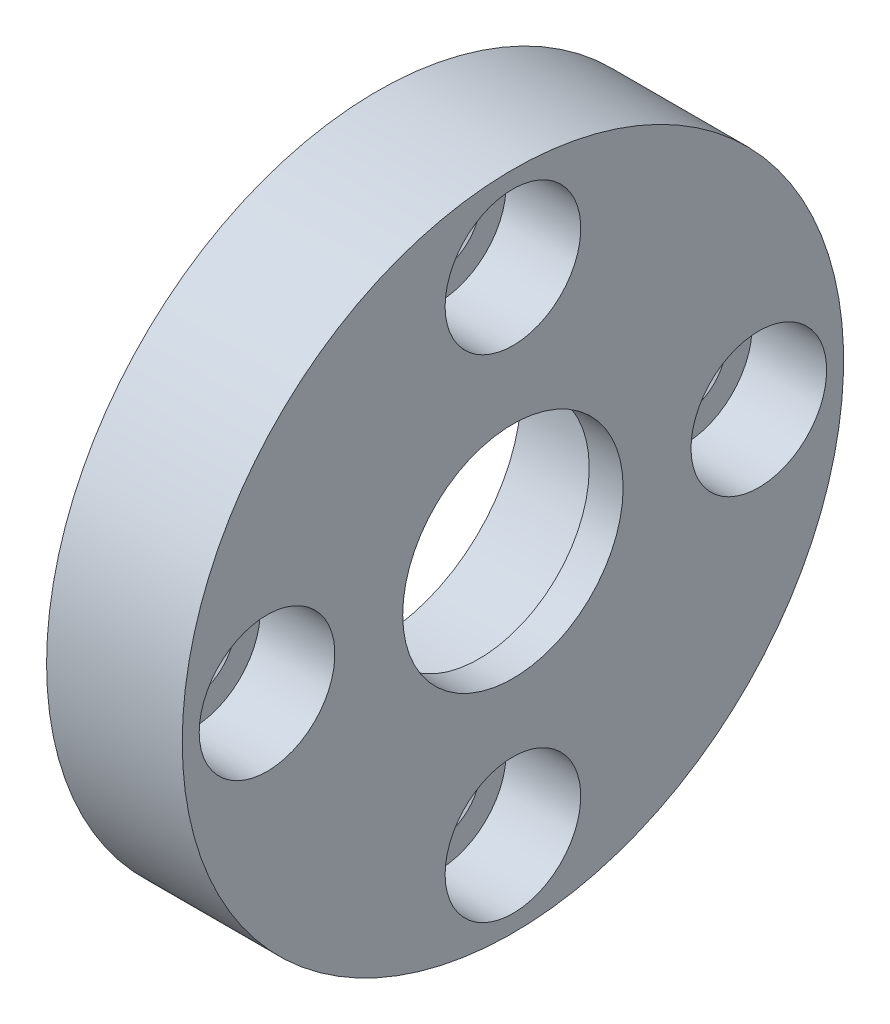
SolidWorks part; units mm, degrees
ref_plane "正面" through (0, 0, 0) normal (0, 0, 1) x (1, 0, 0)
ref_plane "平面" through (0, 0, 0) normal (0, 1, 0) x (1, 0, 0)
ref_plane "右側面" through (0, 0, 0) normal (1, 0, 0) x (0, 0, -1)
ref_plane "平面1" through (0, 0, 0) normal (0, 0, 1) x (1, 0, 0)
sketch "ｽｹｯﾁ1" plane through (0, 0, 0) normal (0, 0, 1) x (1, 0, 0)
  line L0 (-4, 0) -> (-4, 19.5)
  line L1 (-4, 19.5) -> (4, 19.5)
  line L2 (4, 19.5) -> (4, 0)
  line L3 (4, 0) -> (-4, 0)
  line L4 (4, 0) -> (-4, 0) construction
revolve "回転1" add sketch "ｽｹｯﾁ1" angle 360 about L4
ref_plane "平面2" through (0, 0, 0) normal (0, 0, 1) x (1, 0, 0)
sketch "ｽｹｯﾁ2" plane through (0, 0, 0) normal (0, 0, 1) x (1, 0, 0)
  line L0 (-4, 0) -> (-4, 8.5)
  line L1 (-4, 8.5) -> (2, 8.5)
  line L2 (2, 8.5) -> (2, 6.5)
  line L3 (2, 6.5) -> (4, 6.5)
  line L4 (4, 6.5) -> (4, 0)
  line L5 (4, 0) -> (-4, 0)
  line L6 (4, 0) -> (-4, 0) construction
revolve "ｶｯﾄ - 回転1" cut sketch "ｽｹｯﾁ2" angle 360 about L6
ref_plane "平面3" through (0, 0, 0) normal (0, 0, 1) x (1, 0, 0)
sketch "ｽｹｯﾁ3" plane through (0, 0, 0) normal (0, 0, 1) x (1, 0, 0)
  line L0 (-4, 14.5) -> (-4, 17)
  line L1 (-4, 17) -> (-3.567, 16.567)
  line L2 (-3.567, 16.567) -> (-0.833, 16.567)
  line L3 (-0.833, 16.567) -> (-0.4, 17)
  line L4 (-0.4, 17) -> (-0.4, 18.5)
  line L5 (-0.4, 18.5) -> (4, 18.5)
  line L6 (4, 18.5) -> (4, 14.5)
  line L7 (4, 14.5) -> (-4, 14.5)
  line L8 (4, 14.5) -> (-4, 14.5) construction
revolve "ｶｯﾄ - 回転2" cut sketch "ｽｹｯﾁ3" angle 360 about L8
ref_plane "平面4" through (0, 0, 14.5) normal (0, 0, 1) x (1, 0, 0)
sketch "ｽｹｯﾁ4" plane through (0, 0, 14.5) normal (0, 0, 1) x (1, 0, 0)
  line L0 (-4, 0) -> (-4, 2.5)
  line L1 (-4, 2.5) -> (-3.567, 2.067)
  line L2 (-3.567, 2.067) -> (-0.833, 2.067)
  line L3 (-0.833, 2.067) -> (-0.4, 2.5)
  line L4 (-0.4, 2.5) -> (-0.4, 4)
  line L5 (-0.4, 4) -> (4, 4)
  line L6 (4, 4) -> (4, 0)
  line L7 (4, 0) -> (-4, 0)
  line L8 (4, 0) -> (-4, 0) construction
revolve "ｶｯﾄ - 回転3" cut sketch "ｽｹｯﾁ4" angle 360 about L8
ref_plane "平面5" through (0, 0, 0) normal (0, 0, 1) x (1, 0, 0)
sketch "ｽｹｯﾁ5" plane through (0, 0, 0) normal (0, 0, 1) x (1, 0, 0)
  line L0 (-4, -14.5) -> (-4, -12)
  line L1 (-4, -12) -> (-3.567, -12.433)
  line L2 (-3.567, -12.433) -> (-0.833, -12.433)
  line L3 (-0.833, -12.433) -> (-0.4, -12)
  line L4 (-0.4, -12) -> (-0.4, -10.5)
  line L5 (-0.4, -10.5) -> (4, -10.5)
  line L6 (4, -10.5) -> (4, -14.5)
  line L7 (4, -14.5) -> (-4, -14.5)
  line L8 (4, -14.5) -> (-4, -14.5) construction
revolve "ｶｯﾄ - 回転4" cut sketch "ｽｹｯﾁ5" angle 360 about L8
ref_plane "平面6" through (0, 0, -14.5) normal (0, 0, 1) x (1, 0, 0)
sketch "ｽｹｯﾁ6" plane through (0, 0, -14.5) normal (0, 0, 1) x (1, 0, 0)
  line L0 (-4, 0) -> (-4, 2.5)
  line L1 (-4, 2.5) -> (-3.567, 2.067)
  line L2 (-3.567, 2.067) -> (-0.833, 2.067)
  line L3 (-0.833, 2.067) -> (-0.4, 2.5)
  line L4 (-0.4, 2.5) -> (-0.4, 4)
  line L5 (-0.4, 4) -> (4, 4)
  line L6 (4, 4) -> (4, 0)
  line L7 (4, 0) -> (-4, 0)
  line L8 (4, 0) -> (-4, 0) construction
revolve "ｶｯﾄ - 回転5" cut sketch "ｽｹｯﾁ6" angle 360 about L8
